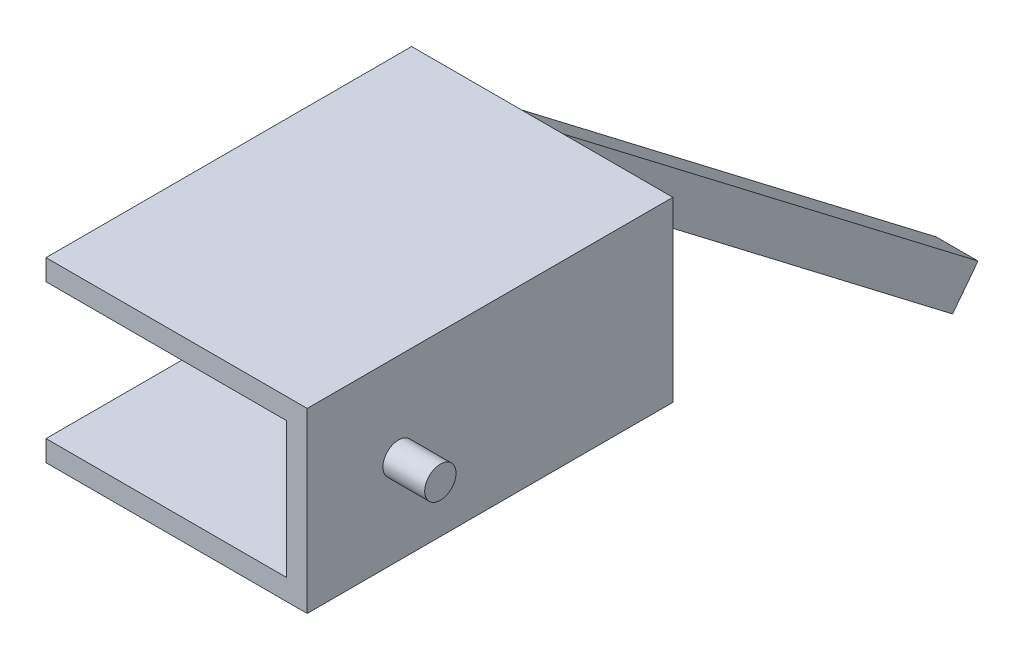
SolidWorks part; units mm, degrees
ref_plane "Front Plane" through (0, 0, 0) normal (0, 0, 1) x (1, 0, 0)
ref_plane "Top Plane" through (0, 0, 0) normal (0, 1, 0) x (1, 0, 0)
ref_plane "Right Plane" through (0, 0, 0) normal (1, 0, 0) x (0, 0, -1)
sketch "Sketch2" plane through (0, 0, 0) normal (0, 0, 1) x (1, 0, 0)
  line L1 (-12.1415, 10.9151) -> (12.8585, 10.9151)
  line L2 (-12.1415, 10.9151) -> (-12.1415, -6.0849)
  line L3 (-12.1415, -6.0849) -> (12.8585, -6.0849)
  line L4 (12.8585, 10.9151) -> (12.8585, -6.0849)
  dimension "D1" = 25
  dimension "D2" = 17
extrude "Boss-Extrude1" add sketch "Sketch2" along normal blind 35 contours L1 L4 L3 L2
sketch "Sketch3" plane through (-12.1415, 0, 0) normal (-1, 0, 0) x (0, 0, 1)
  line L0 (0, 10.9151) -> (-39.7086, -19.4696)
  line L1 (-39.7086, -19.4696) -> (-37.2778, -22.6463)
  line L2 (-37.2778, -22.6463) -> (0, 5.8784)
  line L3 (0, 10.9151) -> (0, -6.0849) construction
  line L4 (0, 5.8784) -> (0, 10.9151)
  dimension "D1" = 50
  dimension "D2" = 4
extrude "Boss-Extrude2" add sketch "Sketch3" against normal mid plane 4 from offset 12.5 contours L1 L2 L4 L0 offset against normal yes
sketch "Sketch4" plane through (-12.1415, 0, 0) normal (-1, 0, 0) x (0, 0, 1)
  line L0 (35, 10.9151) -> (35, -6.0849) construction
  line L1 (9, 7.4151) -> (35, 7.4151)
  line L2 (9, 7.4151) -> (9, -2.5849)
  line L3 (9, -2.5849) -> (35, -2.5849)
  line L4 (35, 7.4151) -> (35, -2.5849)
  line L5 (35, -6.0849) -> (0, -6.0849) construction
  line L7 (35, 10.9151) -> (0, 10.9151) construction
  dimension "D1" = 10
  dimension "D2" = 26
  dimension "D3" = 3.5
  dimension "D4" = 3.5
extrude "Cut-Extrude1" cut sketch "Sketch4" against normal blind 10
sketch "Sketch5" plane through (0, 0, 35) normal (0, 0, 1) x (1, 0, 0)
  line L0 (-12.1415, -2.5849) -> (-12.1415, -6.0849) construction
  line L10 (10.8585, 8.9151) -> (-12.1415, 8.9151)
  line L11 (10.8585, 8.9151) -> (10.8585, -4.0849)
  line L12 (10.8585, -4.0849) -> (-12.1415, -4.0849)
  line L13 (-12.1415, 8.9151) -> (-12.1415, -4.0849)
  line L14 (-12.1415, 10.9151) -> (12.8585, 10.9151) construction
  point P0 (-0.6415, 2.6651)
  point P5 (-0.6415, 2.6651)
  dimension "D1" = 23
  dimension "D2" = 13
  dimension "D3" = 2
extrude "Cut-Extrude2" cut sketch "Sketch5" against normal blind 31
sketch "Sketch6" plane through (12.8585, 0, 0) normal (1, 0, 0) x (0, 0, -1)
  line L0 (-35, 10.9151) -> (-17.5, -6.0849) construction
  line L1 (-35, -6.0849) -> (0, -6.0849) construction
  line L2 (-17.5, -6.0849) -> (-17.5, 10.9151) construction
  line L3 (-35, 10.9151) -> (0, 10.9151) construction
  line L4 (-17.5, 10.9151) -> (-35, -6.0849) construction
  circle A0 centre (-26.2516, 2.4266) radius 1.5
  dimension "D1" = 3
extrude "Boss-Extrude4" add sketch "Sketch6" along normal blind 4
